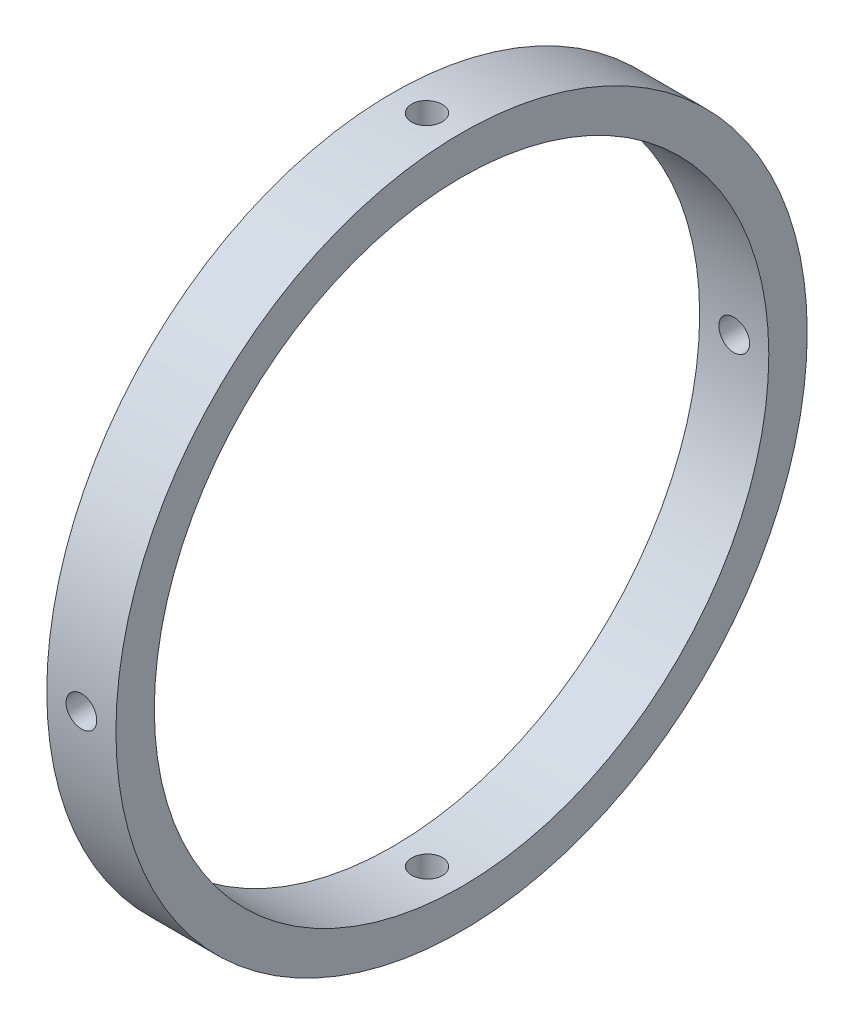
SolidWorks part; units mm, degrees
ref_plane "Front Plane" through (0, 0, 0) normal (0, 0, 1) x (1, 0, 0)
ref_plane "Top Plane" through (0, 0, 0) normal (0, 1, 0) x (1, 0, 0)
ref_plane "Right Plane" through (0, 0, 0) normal (1, 0, 0) x (0, 0, -1)
sketch "Ring Sketch" plane through (0, 0, 0) normal (0, 0, 1) x (1, 0, 0)
  line L0 (-108, 0) -> (12, 0) construction
  line L1 (-57, 80) -> (-39, 80)
  line L2 (-39, 80) -> (-39, 90)
  line L3 (-39, 90) -> (-57, 90)
  line L4 (-57, 90) -> (-57, 80)
revolve "Ring" add sketch "Ring Sketch" angle 360 about L0
ref_axis "Engine Axis" through (-38.1, 0, 0) along (-1, 0, 0)
sketch "Bushing Bore Sketch" plane through (0, 0, 0) normal (0, 0, 1) x (1, 0, 0)
  line L0 (-48, 70) -> (-48, 100) construction
  line L1 (-48, 79) -> (-44, 79)
  line L2 (-44, 79) -> (-44, 91)
  line L3 (-44, 91) -> (-48, 91)
  line L4 (-48, 91) -> (-48, 79)
revolve "Bushing Bore" cut sketch "Bushing Bore Sketch" angle 360 about L0
pattern_circular "Bushing Bores x4" count 4 over 360 about axis through (-38.1, 0, 0) along (-1, 0, 0) of "Bushing Bore"
